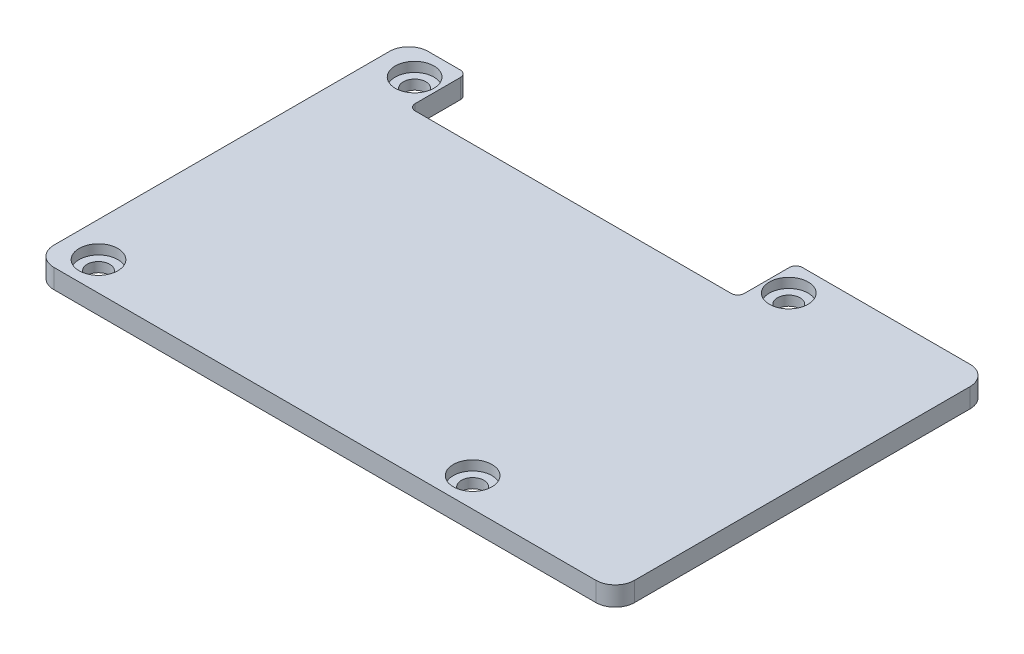
SolidWorks part; units mm, degrees
ref_plane "Front Plane" through (0, 0, 0) normal (0, 0, 1) x (1, 0, 0)
ref_plane "Top Plane" through (0, 0, 0) normal (0, 1, 0) x (1, 0, 0)
ref_plane "Right Plane" through (0, 0, 0) normal (1, 0, 0) x (0, 0, -1)
sketch "Sketch1" plane through (0, 0, 0) normal (0, 1, 0) x (1, 0, 0)
  line L1 (45, -29) -> (-45, -29)
  line L2 (45, -29) -> (45, 29)
  line L3 (45, 29) -> (-45, 29)
  line L4 (-45, -29) -> (-45, 29)
  line L5 (45, -29) -> (-45, 29) construction
  line L6 (45, 29) -> (-45, -29) construction
  point P0 (0, 0)
  dimension "D1" = 58
  dimension "D2" = 90
extrude "Boss-Extrude1" add sketch "Sketch1" along normal blind 3
fillet "Fillet1" radius 3 4 edges at (-45, 1.5, 29) (45, 1.5, 29) (45, 1.5, -29) (-45, 1.5, -29)
sketch "Sketch2" plane through (0, 3, 0) normal (0, 1, 0) x (1, 0, 0)
  line L0 (42, 29) -> (-42, 29) construction
  line L1 (-36, 20) -> (15, 20)
  line L2 (-36, 20) -> (-36, 29)
  line L3 (-36, 29) -> (15, 29)
  line L4 (15, 20) -> (15, 29)
  dimension "D1" = 51
  dimension "D2" = 9
  dimension "D3" = 9
extrude "Cut-Extrude1" cut sketch "Sketch2" against normal up to next
fillet "Fillet3" radius 1 4 edges at (15, 1.5, -20) (15, 1.5, -29) (-36, 1.5, -29) (-36, 1.5, -20)
sketch "Sketch3" plane through (0, 3, 0) normal (0, 1, 0) x (1, 0, 0)
  line L0 (-45, 24.5) -> (45, 24.5) construction
  line L1 (-45, 26) -> (-45, -26) construction
  line L2 (45, -26) -> (45, 26) construction
  line L3 (-36, 28) -> (-36, 21) construction
  circle A0 centre (-39.6, 24.5) radius 1.75
  circle A1 centre (18.4, 24.5) radius 1.75
  dimension "D1" = 3.5
  dimension "D2" = 3.5
  dimension "D3" = 58
  dimension "D5" = 3.6
  dimension "D4" = 24.5
extrude "Cut-Extrude2" cut sketch "Sketch3" against normal up to next
mirror "Mirror1" about plane through (0, 0, 0) normal (0, 0, 1) of "Cut-Extrude2"
sketch "Sketch4" plane through (0, 3, 0) normal (0, 1, 0) x (1, 0, 0)
  circle A0 centre (-39.6, 24.5) radius 3
  circle A1 centre (18.4, 24.5) radius 3
  dimension "D1" = 6
  dimension "D2" = 6
extrude "Cut-Extrude4" cut sketch "Sketch4" against normal blind 1.5
mirror "Mirror2" about plane through (0, 0, 0) normal (0, 0, 1) of "Cut-Extrude4"
